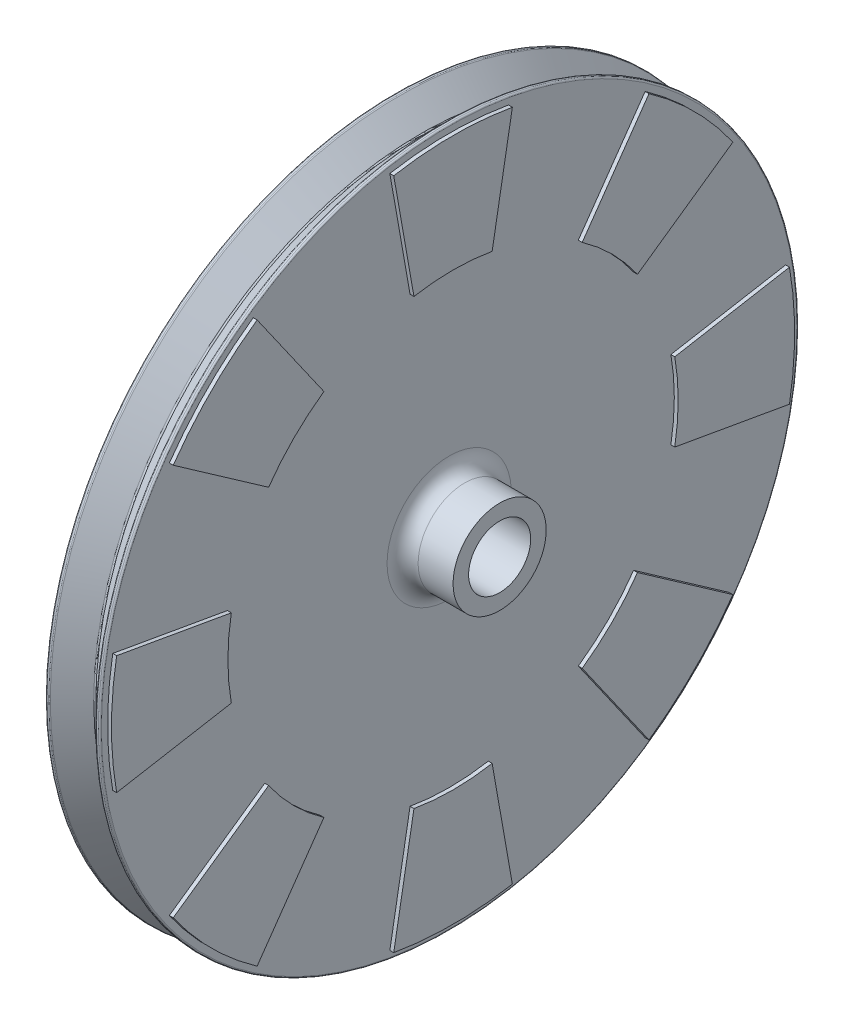
SolidWorks part; units mm, degrees
ref_plane "Face" through (0, 0, 0) normal (0, 0, 1) x (1, 0, 0)
ref_plane "Dessus" through (0, 0, 0) normal (0, 1, 0) x (1, 0, 0)
ref_plane "Droite" through (0, 0, 0) normal (1, 0, 0) x (0, 0, -1)
sketch "Esquisse1" plane through (0, 0, 0) normal (0, 0, 1) x (1, 0, 0)
  line L1 (-3, 45) -> (0, 42)
  line L2 (0, 0) -> (-3.5, 0)
  line L3 (3.5, 8) -> (3.5, 45)
  line L4 (3.5, 45) -> (3, 45)
  line L5 (-3.5, 0) -> (-3.5, 45)
  line L6 (0, 42) -> (3, 45)
  line L7 (-3, 45) -> (-3.5, 45)
  line L8 (5.5, 6) -> (10, 6)
  line L9 (10, 6) -> (10, 4)
  line L10 (10, 4) -> (0, 4)
  line L11 (0, 4) -> (0, 0)
  line L12 (0, 0) -> (68.6205, 0) construction
  arc A0 (3.5, 8) -> (5.5, 6) centre (5.5, 8) ccw
  dimension "D8" = 2
  dimension "D1" = 10
  dimension "D2" = 7
  dimension "D3" = 4
  dimension "D4" = 0.5
  dimension "D5" = 0.5
  dimension "D6" = 45
  dimension "D7" = 2
  dimension "D9" = 45
revolve "Révolution2" add sketch "Esquisse1" angle 360 about L12
sketch "Esquisse2" plane through (3.5, 0, 0) normal (1, 0, 0) x (0, 0, -1)
  line L0 (0, 0) -> (0, 48.3793) construction
  line L1 (5.0358, 28.5594) -> (7.6405, 43.3315)
  line L2 (-5.0358, 28.5594) -> (-7.6405, 43.3315)
  arc A0 (7.6405, 43.3315) -> (-7.6405, 43.3315) centre (0, 0) ccw
  arc A1 (5.0358, 28.5594) -> (-5.0358, 28.5594) centre (0, 0) ccw
  dimension "D2" = 44
  dimension "D1" = 20
  dimension "D3" = 15
extrude "Extrusion1" add sketch "Esquisse2" along normal blind 0.5
pattern_circular "Répétition circulaire1" count 8 over 360 about axis through (0, 0, 0) along (1, 0, 0)
fillet "Congé1" radius 0.2
sketch "Esquisse3" plane through (-3.5, 0, 0) normal (-1, 0, 0) x (0, 0, 1)
  circle A0 centre (-32.0177, 10.7616) radius 2.0238
extrude "Enlèv. mat.-Extru.1" cut sketch "Esquisse3" against normal blind 0.25
